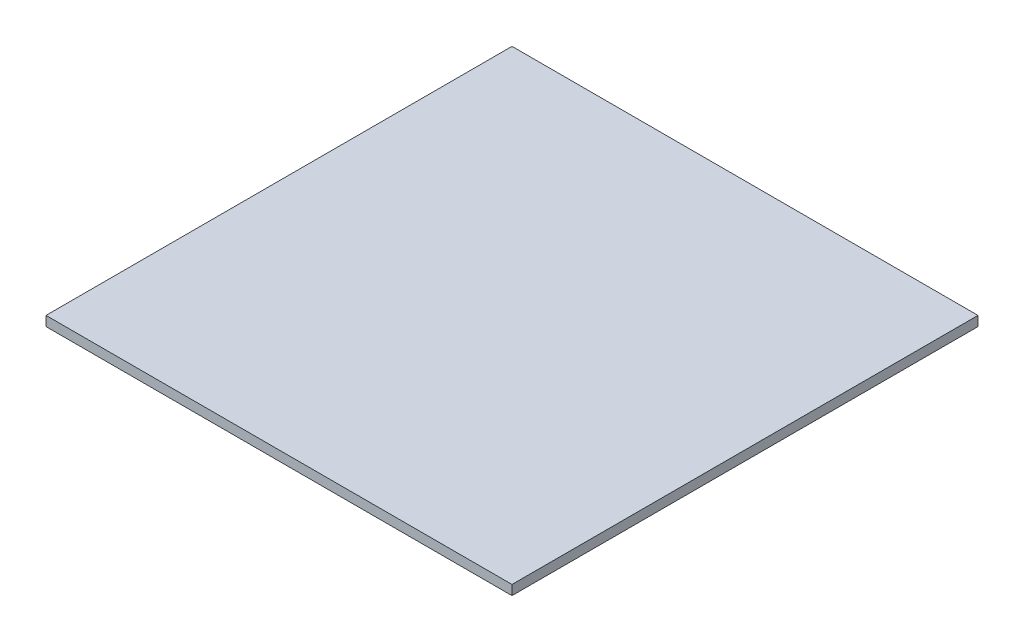
SolidWorks part; units mm, degrees
ref_plane "Front Plane" through (0, 0, 0) normal (0, 0, 1) x (1, 0, 0)
ref_plane "Top Plane" through (0, 0, 0) normal (0, 1, 0) x (1, 0, 0)
ref_plane "Right Plane" through (0, 0, 0) normal (1, 0, 0) x (0, 0, -1)
sketch "Sketch1" plane through (0, 0, 0) normal (0, 1, 0) x (1, 0, 0)
  line L1 (0, 0) -> (152.4, 0)
  line L2 (0, 0) -> (0, 152.4)
  line L3 (0, 152.4) -> (152.4, 152.4)
  line L4 (152.4, 0) -> (152.4, 152.4)
  dimension "D1" = 152.4
  dimension "D2" = 152.4
extrude "Boss-Extrude1" add sketch "Sketch1" along normal blind 3.175
